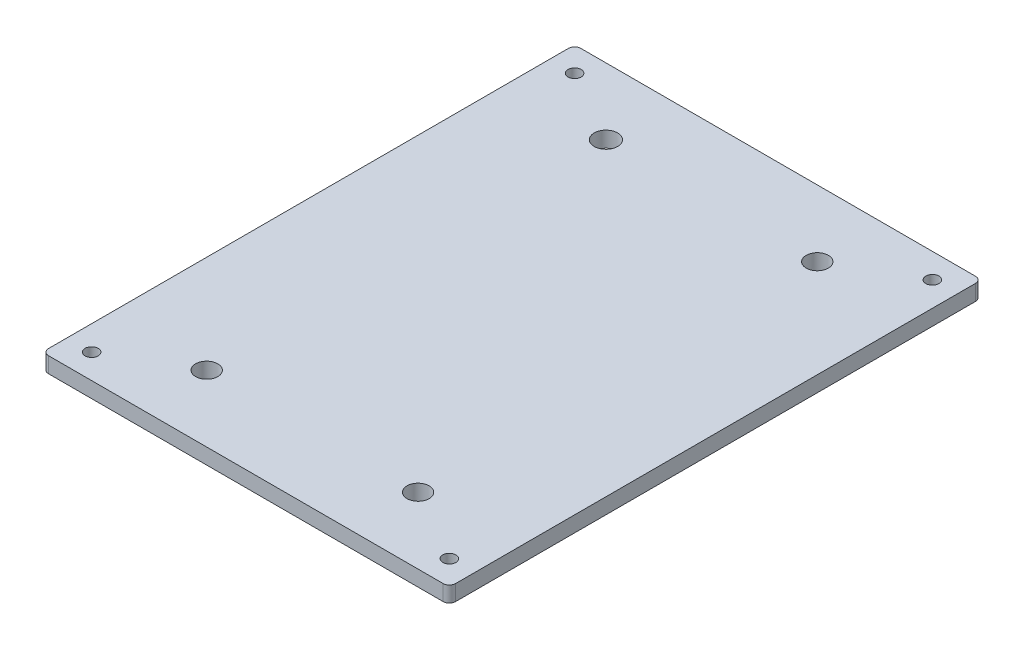
SolidWorks part; units mm, degrees
ref_plane "Front Plane" through (0, 0, 0) normal (0, 0, 1) x (1, 0, 0)
ref_plane "Top Plane" through (0, 0, 0) normal (0, 1, 0) x (1, 0, 0)
ref_plane "Right Plane" through (0, 0, 0) normal (1, 0, 0) x (0, 0, -1)
sketch "Sketch1" plane through (0, 0, 0) normal (0, 1, 0) x (1, 0, 0)
  line L1 (82.55, 107.95) -> (-82.55, 107.95)
  line L2 (82.55, 107.95) -> (82.55, -107.95)
  line L3 (82.55, -107.95) -> (-82.55, -107.95)
  line L4 (-82.55, 107.95) -> (-82.55, -107.95)
  line L5 (82.55, 107.95) -> (-82.55, -107.95) construction
  line L6 (82.55, -107.95) -> (-82.55, 107.95) construction
  point P0 (0, 0)
  dimension "D1" = 215.9
  dimension "D2" = 165.1
extrude "Boss-Extrude1" add sketch "Sketch1" along normal blind 6.35
sketch "Sketch2" plane through (0, 6.35, 0) normal (0, 1, 0) x (1, 0, 0)
  line L0 (82.55, 107.95) -> (-82.55, 107.95) construction
  line L1 (-42.8625, 80.9625) -> (42.8625, 80.9625) construction
  line L2 (-42.8625, 80.9625) -> (-42.8625, -80.9625) construction
  line L3 (-42.8625, -80.9625) -> (42.8625, -80.9625) construction
  line L4 (42.8625, 80.9625) -> (42.8625, -80.9625) construction
  line L5 (-42.8625, 80.9625) -> (42.8625, -80.9625) construction
  line L6 (-42.8625, -80.9625) -> (42.8625, 80.9625) construction
  line L7 (0, 107.95) -> (0, 80.9625) construction
  line L8 (0, 80.9625) -> (0, -80.9625) construction
  line L9 (0, -80.9625) -> (0, -107.95) construction
  line L10 (-82.55, -107.95) -> (82.55, -107.95) construction
  line L11 (42.8625, 0) -> (82.55, 0) construction
  line L12 (82.55, -107.95) -> (82.55, 107.95) construction
  line L13 (-42.8625, 0) -> (-82.55, 0) construction
  line L14 (-82.55, 107.95) -> (-82.55, -107.95) construction
  circle A0 centre (-42.8625, 80.9625) radius 4.7625
  circle A1 centre (-42.8625, -80.9625) radius 4.5
  circle A2 centre (42.8625, -80.9625) radius 4.5
  circle A4 centre (42.8625, 80.9625) radius 4.5
  point P5 (0, 0)
  dimension "D4" = 9.525
  dimension "D2" = 85.725
  dimension "D3" = 161.925
sketch "Sketch3" plane through (0, 6.35, 0) normal (0, 1, 0) x (-1, 0, 0)
  line L0 (72.55, -107.95) -> (72.55, 107.95) construction
  line L1 (-82.55, -107.95) -> (82.55, -107.95) construction
  line L2 (82.55, 107.95) -> (-82.55, 107.95) construction
  line L3 (82.55, 97.95) -> (-82.55, 97.95) construction
  line L4 (82.55, -107.95) -> (82.55, 107.95) construction
  line L5 (-82.55, 107.95) -> (-82.55, -107.95) construction
  line L6 (-72.55, -107.95) -> (-72.55, 107.95) construction
  circle A0 centre (72.55, 97.95) radius 2.665
  circle A1 centre (-72.55, 97.95) radius 2.665
  circle A2 centre (-72.55, -97.95) radius 2.665
  circle A3 centre (72.55, -97.95) radius 2.665
  dimension "D4" = 10
  dimension "D5" = 10
  dimension "D6" = 5.33
  dimension "D1" = 10
  dimension "D2" = 10
  dimension "D3" = 10
extrude "Cut-Extrude2" cut sketch "Sketch3" against normal up to next
fillet "Fillet1" radius 2.54 4 edges at (-82.55, 3.175, -107.95) (82.55, 3.175, -107.95) (82.55, 3.175, 107.95) (-82.55, 3.175, 107.95)
extrude "Cut-Extrude3" cut sketch "Sketch2" against normal up to next
